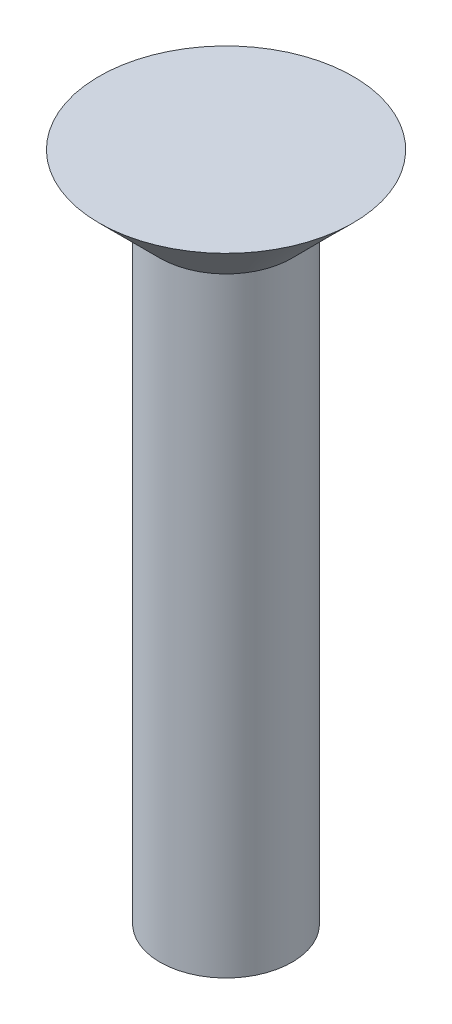
SolidWorks part; units mm, degrees
material "1023 Carbon Steel Sheet (SS)"
ref_plane "Front Plane" through (0, 0, 0) normal (0, 0, 1) x (1, 0, 0)
ref_plane "Top Plane" through (0, 0, 0) normal (0, 1, 0) x (1, 0, 0)
ref_plane "Right Plane" through (0, 0, 0) normal (1, 0, 0) x (0, 0, -1)
sketch "Sketch4" plane through (0, 0, 0) normal (0, 0, 1) x (1, 0, 0)
  line L0 (0, 0) -> (1.3, 0)
  line L1 (55, 0) -> (-55, 0) construction
  line L2 (1.3, 0) -> (1.3, 12)
  line L3 (1.3, 12) -> (2.5, 13.2)
  line L4 (2.5, 13.2) -> (0, 13.2)
  line L5 (0, -55) -> (0, 55) construction
  line L6 (0, 13.2) -> (0, 0)
  dimension "D1" = 1.3
  dimension "D2" = 12
  dimension "D3" = 1.2
  dimension "D4" = 2.5
revolve "Revolve1" add sketch "Sketch4" angle 360 about L6
